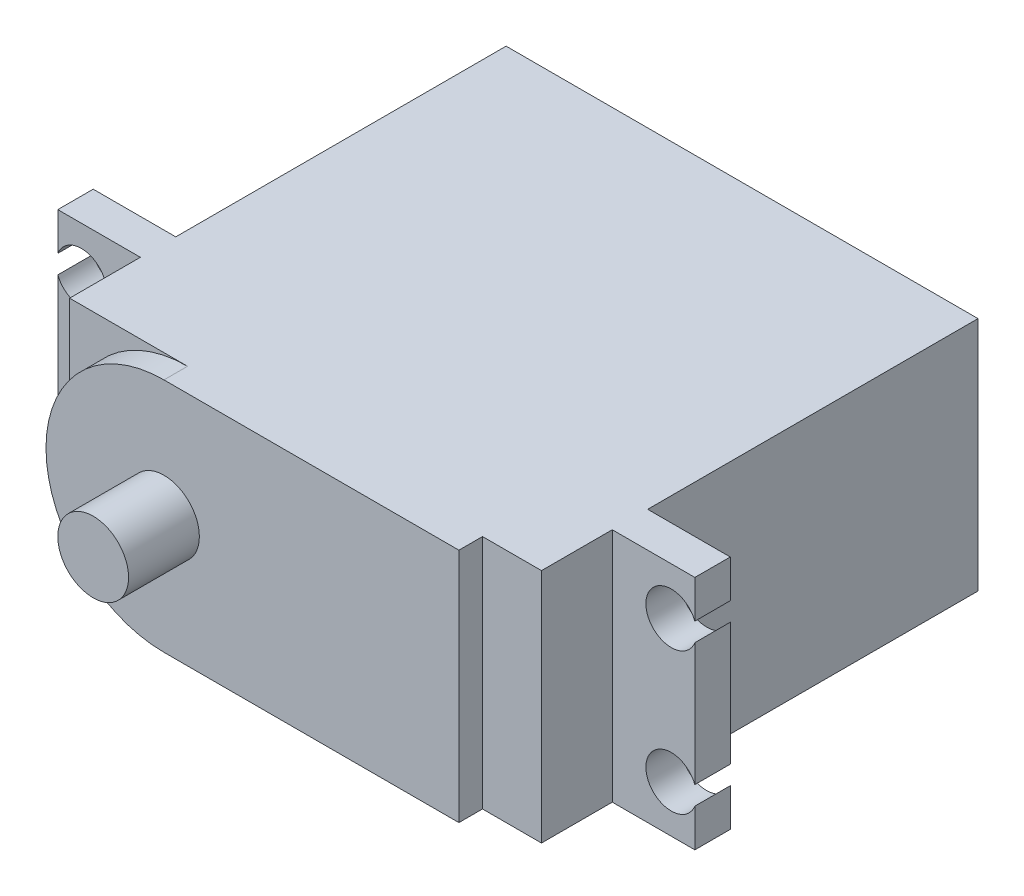
SolidWorks part; units mm, degrees
ref_plane "Front Plane" through (0, 0, 0) normal (0, 0, 1) x (1, 0, 0)
ref_plane "Top Plane" through (0, 0, 0) normal (0, 1, 0) x (1, 0, 0)
ref_plane "Right Plane" through (0, 0, 0) normal (1, 0, 0) x (0, 0, -1)
sketch "Sketch1" plane through (0, 0, 0) normal (0, 0, 1) x (1, 0, 0)
  line L1 (-20, -10) -> (20, -10)
  line L2 (-20, -10) -> (-20, 10)
  line L3 (-20, 10) -> (20, 10)
  line L4 (20, -10) -> (20, 10)
  line L5 (-20, -10) -> (20, 10) construction
  line L6 (-20, 10) -> (20, -10) construction
  point P0 (0, 0)
  dimension "D1" = 20
  dimension "D2" = 40
extrude "Boss-Extrude1" add sketch "Sketch1" along normal blind 37
sketch "Sketch2" plane through (0, 0, 37) normal (0, 0, 1) x (1, 0, 0)
  line L0 (-20, 10) -> (-20, -10) construction
  line L1 (15, 10) -> (15, -10)
  line L2 (20, 10) -> (-20, 10) construction
  line L3 (-20, -10) -> (20, -10) construction
  line L4 (20, -10) -> (20, 10) construction
  line L5 (-10, 10) -> (15, 10)
  line L6 (-10, -10) -> (15, -10)
  arc A0 (-10, 10) -> (-10, -10) centre (-10, 0) ccw
  point P0 (-10, 0)
  dimension "D1" = 10
  dimension "D2" = 5
extrude "Boss-Extrude2" add sketch "Sketch2" along normal blind 2
sketch "Sketch3" plane through (20, 0, 0) normal (1, 0, 0) x (0, 0, -1)
  line L0 (-37, 10) -> (0, 10) construction
  line L1 (-31, 10) -> (-28, 10)
  line L2 (-31, 10) -> (-31, -10)
  line L3 (-31, -10) -> (-28, -10)
  line L4 (-28, 10) -> (-28, -10)
  line L5 (-37, -10) -> (0, -10) construction
  line L6 (0, -10) -> (0, 10) construction
  dimension "D1" = 31
  dimension "D2" = 3
extrude "Boss-Extrude3" add sketch "Sketch3" along normal blind 7
sketch "Sketch4" plane through (-20, 0, 0) normal (-1, 0, 0) x (0, 0, 1)
  line L0 (37, -10) -> (0, -10) construction
  line L1 (28, 10) -> (31, 10)
  line L2 (28, 10) -> (28, -10)
  line L3 (28, -10) -> (31, -10)
  line L4 (31, 10) -> (31, -10)
  line L5 (0, 10) -> (0, -10) construction
  dimension "D1" = 31
  dimension "D2" = 3
extrude "Boss-Extrude4" add sketch "Sketch4" along normal blind 7
sketch "Sketch8" plane through (0, 0, 31) normal (0, 0, 1) x (1, 0, 0)
  line L0 (-27, 10) -> (-20, 10) construction
  line L3 (-27, -10) -> (-27, 10) construction
  circle A0 centre (-25, 6) radius 2.15
  point P0 (-25, 6)
  point P12 (0, 0)
  dimension "D1" = 4
  dimension "D2" = 2
extrude "Cut-Extrude9" cut sketch "Sketch8" against normal blind 7 contours A0
sketch "Sketch9" plane through (0, 0, 31) normal (0, 0, 1) x (1, 0, 0)
  line L0 (-27, -10) -> (-20, -10) construction
  line L1 (-27, -10) -> (-27, 5.211) construction
  circle A0 centre (-25, -6) radius 2.15
  point P0 (-25, -6)
  dimension "D3" = 4.3
  dimension "D1" = 4
  dimension "D2" = 2
extrude "Cut-Extrude10" cut sketch "Sketch9" against normal up to next
sketch "Sketch10" plane through (0, 0, 31) normal (0, 0, 1) x (1, 0, 0)
  line L0 (27, 10) -> (27, -10) construction
  line L1 (27, -10) -> (20, -10) construction
  line L2 (27, 10) -> (20, 10) construction
  circle A0 centre (25, 6) radius 2.15
  circle A1 centre (25, -6) radius 2.15
  point P0 (25, 6)
  point P1 (25, -6)
  dimension "D5" = 4.3
  dimension "D6" = 4.3
  dimension "D1" = 2
  dimension "D2" = 2
  dimension "D3" = 4
  dimension "D4" = 4
extrude "Cut-Extrude11" cut sketch "Sketch10" against normal up to next
sketch "Sketch11" plane through (0, 0, 39) normal (0, 0, 1) x (1, 0, 0)
  circle A0 centre (-10, 0) radius 3
  point P0 (-10, 0)
  dimension "D1" = 6
extrude "Boss-Extrude5" add sketch "Sketch11" along normal blind 6
